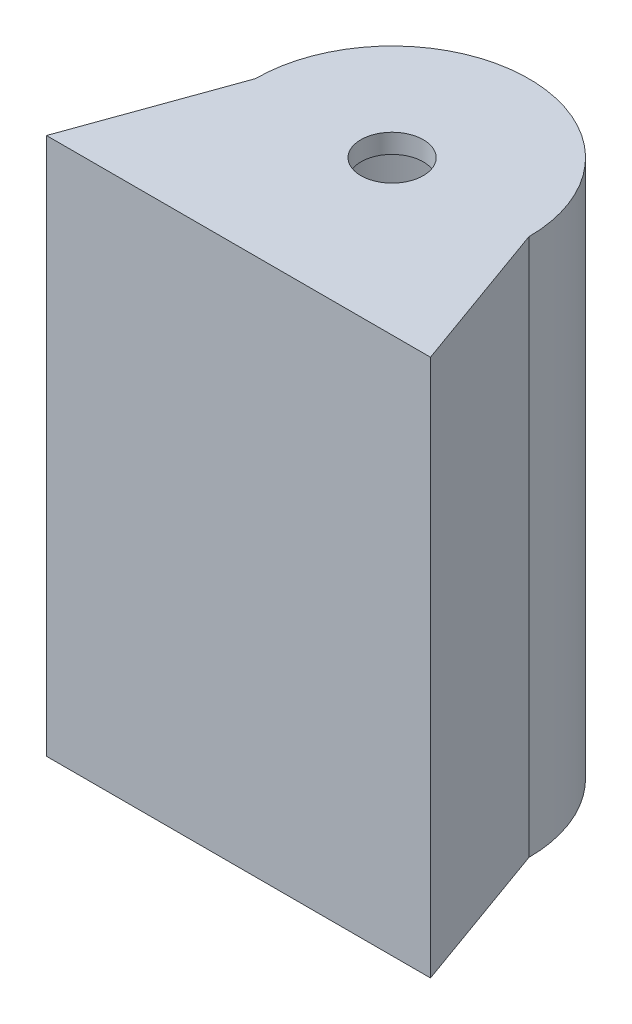
SolidWorks part; units mm, degrees
ref_plane "Front Plane" through (0, 0, 0) normal (0, 0, 1) x (1, 0, 0)
ref_plane "Top Plane" through (0, 0, 0) normal (0, 1, 0) x (1, 0, 0)
ref_plane "Right Plane" through (0, 0, 0) normal (1, 0, 0) x (0, 0, -1)
sketch "Sketch2" plane through (0, 0, 0) normal (0, 1, 0) x (1, 0, 0)
  line L0 (-12.75, 0) -> (12.75, 0)
  line L1 (0, 0) -> (0, -16)
  line L2 (-20, -16) -> (20, -16)
  line L3 (20, -16) -> (14.25, 0)
  line L4 (-14.25, 0) -> (-20, -16)
  circle A2 centre (0, 0) radius 12.75
  arc A3 (14.25, 0) -> (-14.25, 0) centre (0, 0) ccw
  point P4 (0, 0)
  point P10 (0, -16)
  dimension "D4" = 1.5
  dimension "D5" = 25.5
  dimension "D1" = 28.5
  dimension "D2" = 16
  dimension "D3" = 40
  dimension "D6" = 1.5
extrude "Boss-Extrude1" add sketch "Sketch2" against normal blind 56
sketch "Sketch3" plane through (0, 0, 0) normal (0, 1, 0) x (1, 0, 0)
  circle A0 centre (0, 0) radius 12.75
  circle A1 centre (0, 0) radius 3.25
  dimension "D1" = 25.5
  dimension "D2" = 6.5
extrude "Boss-Extrude2" add sketch "Sketch3" against normal blind 2
